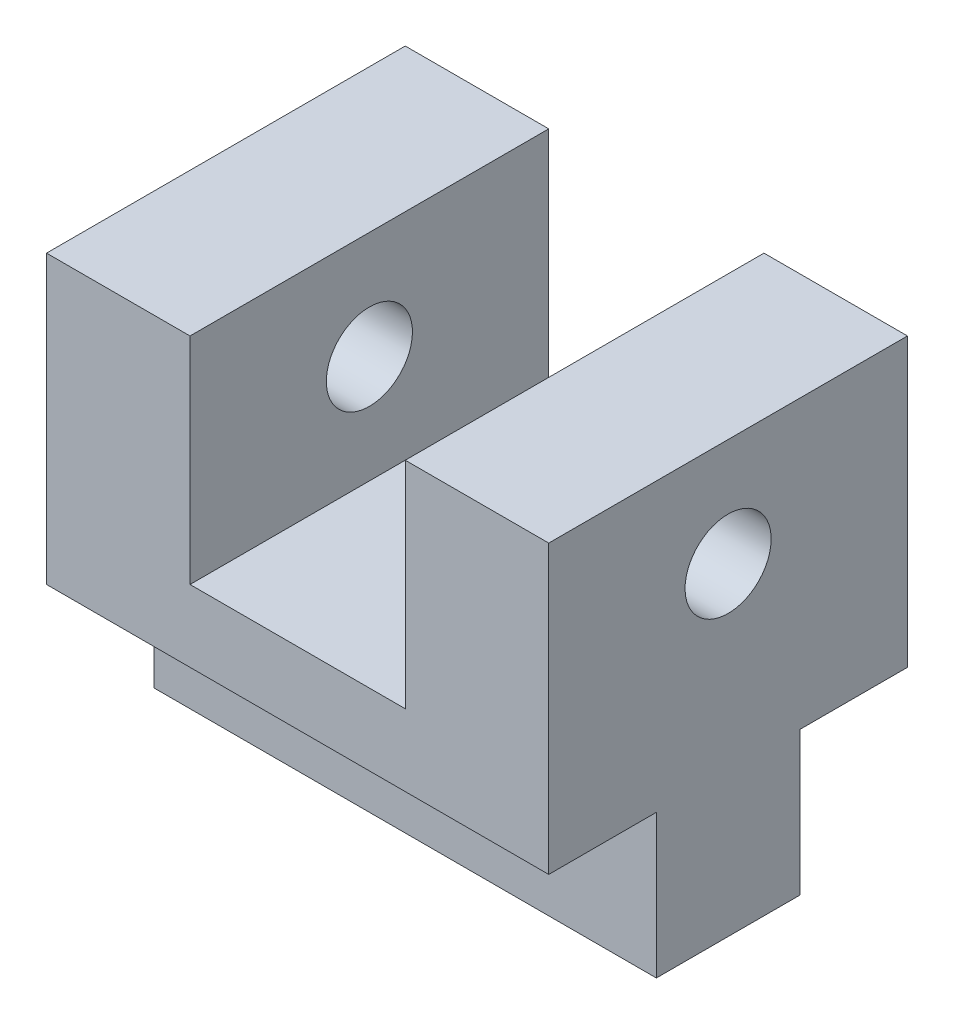
SolidWorks part; units mm, degrees
ref_plane "Front Plane" through (0, 0, 0) normal (0, 0, 1) x (1, 0, 0)
ref_plane "Top Plane" through (0, 0, 0) normal (0, 1, 0) x (1, 0, 0)
ref_plane "Right Plane" through (0, 0, 0) normal (1, 0, 0) x (0, 0, -1)
sketch "Sketch1" plane through (0, 0, 0) normal (0, 0, 1) x (1, 0, 0)
  line L0 (0, 9.1051) -> (0, -5.8949)
  line L1 (-25, 9.1051) -> (-15, 9.1051)
  line L2 (-25, 9.1051) -> (-25, -10.8949)
  line L3 (-25, -10.8949) -> (10, -10.8949)
  line L4 (10, 9.1051) -> (10, -10.8949)
  line L5 (0, -5.8949) -> (-15, -5.8949)
  line L6 (-15, -5.8949) -> (-15, 9.1051)
  line L7 (0, 9.1051) -> (10, 9.1051)
  dimension "D1" = 35
  dimension "D2" = 20
  dimension "D3" = 15
  dimension "D4" = 15
  dimension "D5" = 10
extrude "Boss-Extrude1" add sketch "Sketch1" against normal blind 25
sketch "Sketch4" plane through (10, 0, 0) normal (1, 0, 0) x (0, 0, -1)
  line L2 (25, -10.8949) -> (25, 9.1051) construction
  circle A0 centre (12.5, 1.6051) radius 3
  point P7 (0, 1.9708)
  point P8 (0, 0)
  dimension "D1" = 6
  dimension "D2" = 12.5
extrude "Cut-Extrude1" cut sketch "Sketch4" against normal blind 40
sketch "Sketch5" plane through (0, -10.8949, 0) normal (0, -1, 0) x (1, 0, 0)
  line L0 (-25, -25) -> (10, -25) construction
  line L1 (-25, -7.5) -> (10, -7.5)
  line L2 (-25, -7.5) -> (-25, -17.5)
  line L3 (-25, -17.5) -> (10, -17.5)
  line L4 (10, -7.5) -> (10, -17.5)
  line L5 (-25, -25) -> (-25, 0) construction
  dimension "D1" = 10
  dimension "D2" = 7.5
  dimension "D3" = 35
  dimension "D4" = 0
extrude "Boss-Extrude3" add sketch "Sketch5" along normal blind 10
